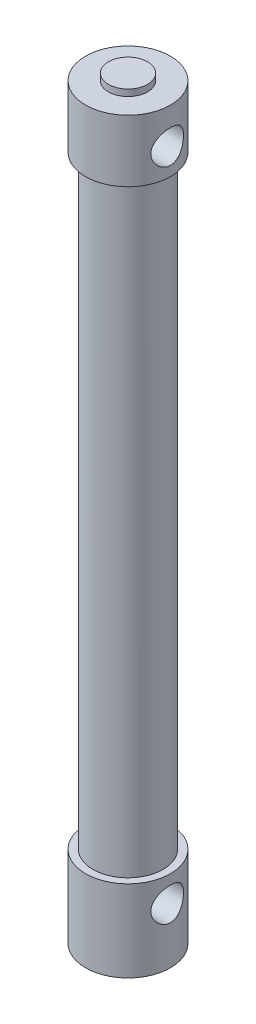
SolidWorks part; units mm, degrees
ref_plane "前视基准面" through (0, 0, 0) normal (0, 0, 1) x (1, 0, 0)
ref_plane "上视基准面" through (0, 0, 0) normal (0, 1, 0) x (1, 0, 0)
ref_plane "右视基准面" through (0, 0, 0) normal (1, 0, 0) x (0, 0, -1)
sketch "草图1" plane through (0, 0, 0) normal (0, 1, 0) x (1, 0, 0)
  circle A0 centre (0, 0) radius 10.75
  circle A1 centre (0, 0) radius 9
  dimension "D1" = 21.5
  dimension "D2" = 18
extrude "拉伸1" add sketch "草图1" along normal blind 185
sketch "草图3" plane through (0, 0, 0) normal (1, 0, 0) x (0, 0, -1)
  line L0 (0, 185) -> (0, 208.8318) construction
  line L1 (10.75, 185) -> (-10.75, 185) construction
  line L2 (0, 185) -> (-13, 185)
  line L3 (-13, 185) -> (-13, 204)
  line L4 (-13, 204) -> (-6, 204)
  line L5 (-6, 204) -> (-6, 206)
  line L6 (-6, 206) -> (0, 206)
  line L7 (0, 185) -> (0, 206)
  dimension "D1" = 13
  dimension "D2" = 19
  dimension "D3" = 6
  dimension "D4" = 2
revolve "旋转1" add sketch "草图3" angle 360 about L0
sketch "草图4" plane through (0, 0, 0) normal (1, 0, 0) x (0, 0, -1)
  line L0 (0, 0) -> (0, -27) construction
  line L1 (5, 0) -> (13, 0)
  line L2 (13, 0) -> (13, -25)
  line L3 (13, -25) -> (6, -25)
  line L4 (6, -25) -> (6, -27)
  line L5 (6, -27) -> (5, -27)
  line L6 (5, -27) -> (5, 0)
  dimension "D1" = 13
  dimension "D2" = 6
  dimension "D3" = 2
  dimension "D4" = 25
  dimension "D5" = 5
revolve "旋转2" add sketch "草图4" angle 360 about L0
ref_plane "基准面1" through (13, 0, 0) normal (1, 0, 0) x (0, 0, -1)
sketch "草图5" plane through (13, 0, 0) normal (1, 0, 0) x (0, 0, -1)
  line L0 (-10.75, 185) -> (10.75, 185) construction
  line L1 (13, 0) -> (-13, 0) construction
  circle A0 centre (0, 193) radius 5
  circle A1 centre (0, -8) radius 5
  dimension "D1" = 10
  dimension "D2" = 8
  dimension "D3" = 10
  dimension "D4" = 8
extrude "拉伸2" cut sketch "草图5" against normal blind 10
sketch "草图6" plane through (0, -25, 0) normal (0, -1, 0) x (1, 0, 0)
  line L0 (0, 0) -> (4.2918, 0) construction
  line L1 (0, 0) -> (0, -3.463) construction
  circle A0 centre (7, 7) radius 1.0589
  circle A1 centre (-7, 7) radius 1.0589
  circle A2 centre (-7, -7) radius 1.0589
  circle A3 centre (7, -7) radius 1.0589
  dimension "D1" = 14
  dimension "D2" = 14
  dimension "D3" = 14
  dimension "D4" = 14
  dimension "D5" = 7
  dimension "D6" = 7
  dimension "D7" = 7
  dimension "D8" = 7
extrude "拉伸3" cut sketch "草图6" against normal blind 15
